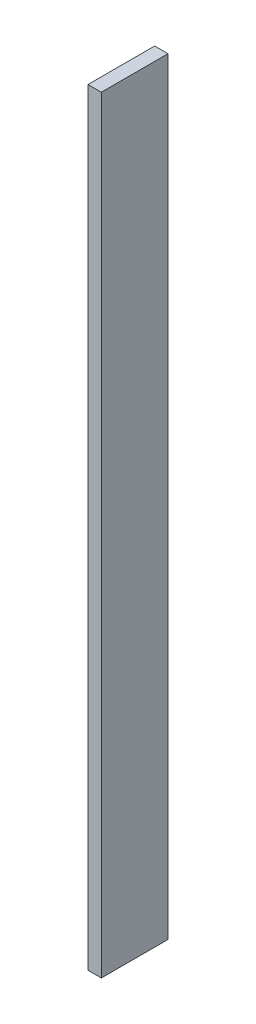
SolidWorks part; units mm, degrees
ref_plane "Front" through (0, 0, 0) normal (0, 0, 1) x (1, 0, 0)
ref_plane "Top" through (0, 0, 0) normal (0, 1, 0) x (1, 0, 0)
ref_plane "Right" through (0, 0, 0) normal (1, 0, 0) x (0, 0, -1)
sketch "Sketch1" plane through (0, 0, 0) normal (0, 1, 0) x (1, 0, 0)
  line L1 (-9.9715, -25.104) -> (0.1885, -25.104)
  line L2 (-9.9715, -25.104) -> (-9.9715, 25.696)
  line L3 (-9.9715, 25.696) -> (0.1885, 25.696)
  line L4 (0.1885, -25.104) -> (0.1885, 25.696)
  line L5 (-9.9715, -25.104) -> (0.1885, 25.696) construction
  line L6 (-9.9715, 25.696) -> (0.1885, -25.104) construction
  point P0 (-4.8915, 0.296)
extrude "Boss-Extrude1" add sketch "Sketch1" along normal blind 584.2
